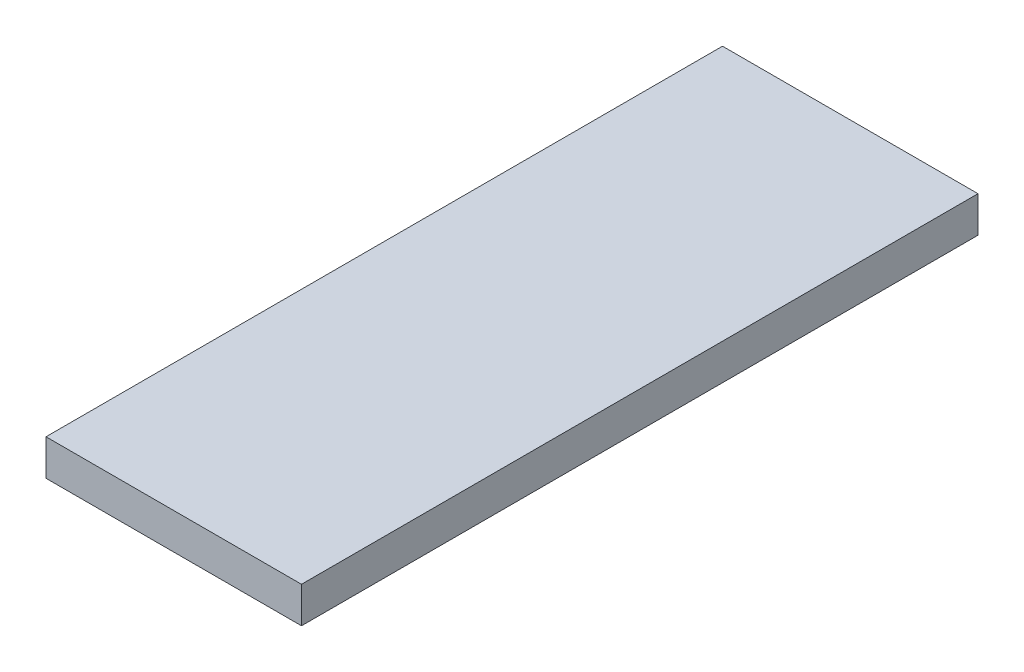
SolidWorks part; units mm, degrees
ref_plane "Front Plane" through (0, 0, 0) normal (0, 0, 1) x (1, 0, 0)
ref_plane "Top Plane" through (0, 0, 0) normal (0, 1, 0) x (1, 0, 0)
ref_plane "Right Plane" through (0, 0, 0) normal (1, 0, 0) x (0, 0, -1)
sketch "Sketch1" plane through (0, 0, 0) normal (0, 0, 1) x (1, 0, 0)
  line L1 (0, 0) -> (355, 0)
  line L2 (0, 0) -> (0, 50)
  line L3 (0, 50) -> (355, 50)
  line L4 (355, 0) -> (355, 50)
  dimension "D1" = 355
  dimension "D2" = 50
extrude "Boss-Extrude1" add sketch "Sketch1" along normal blind 940
